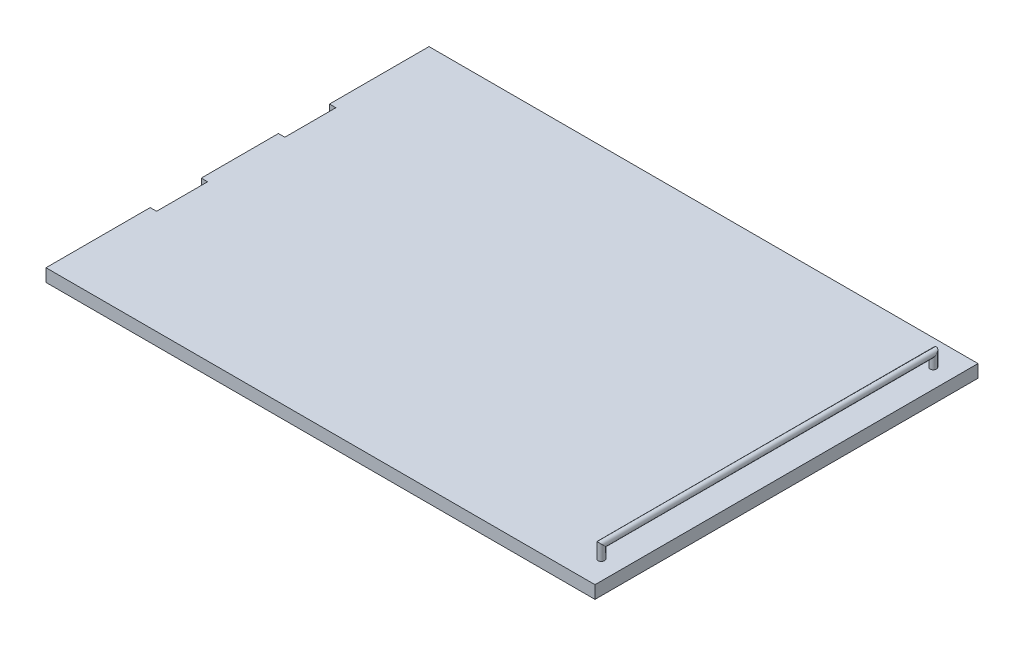
SolidWorks part; units mm, degrees
ref_plane "Front Plane" through (0, 0, 0) normal (0, 0, 1) x (1, 0, 0)
ref_plane "Top Plane" through (0, 0, 0) normal (0, 1, 0) x (1, 0, 0)
ref_plane "Right Plane" through (0, 0, 0) normal (1, 0, 0) x (0, 0, -1)
sketch "Sketch1" plane through (0, 0, 0) normal (0, 1, 0) x (1, 0, 0)
  line L1 (-546.1, -381) -> (546.1, -381)
  line L2 (-546.1, -381) -> (-546.1, 381)
  line L3 (-546.1, 381) -> (546.1, 381)
  line L4 (546.1, -381) -> (546.1, 381)
  line L5 (-546.1, -381) -> (546.1, 381) construction
  line L6 (-546.1, 381) -> (546.1, -381) construction
  point P0 (0, 0)
  dimension "D1" = 762
  dimension "D2" = 1092.2
extrude "Boss-Extrude1" add sketch "Sketch1" along normal blind 25.4
sketch "Sketch2" plane through (0, 25.4, 0) normal (0, 1, 0) x (1, 0, 0)
  line L0 (-546.1, 183.0439) -> (-546.1, 132.2439)
  line L1 (-546.1, 381) -> (-546.1, -381) construction
  line L2 (-546.1, 132.2439) -> (-546.1, 81.4439)
  line L3 (-546.1, -122.9273) -> (-546.1, -173.7273)
  line L6 (-546.1, -122.9273) -> (-546.1, -72.1273)
  line L9 (-546.1, 183.0439) -> (-533.4, 183.0439)
  line L10 (-533.4, 183.0439) -> (-533.4, 81.4439)
  line L11 (-533.4, 81.4439) -> (-546.1, 81.4439)
  line L12 (-546.1, -72.1273) -> (-533.4, -72.1273)
  line L13 (-533.4, -72.1273) -> (-533.4, -173.7273)
  line L14 (-533.4, -173.7273) -> (-546.1, -173.7273)
  dimension "D1" = 50.8
  dimension "D2" = 12.7
  dimension "D3" = 12.7
extrude "Cut-Extrude1" cut sketch "Sketch2" against normal through all
ref_plane "Plane1" through (508, 0, 0) normal (1, 0, 0) x (0, 0, -1)
sketch "Sketch3" plane through (508, 0, 0) normal (1, 0, 0) x (0, 0, -1)
  line L1 (-381, 25.4) -> (381, 25.4) construction
  line L3 (-330.2, 25.4) -> (-330.2, 50.8)
  line L4 (-330.2, 50.8) -> (330.2, 50.8)
  line L5 (330.2, 50.8) -> (330.2, 25.4)
  dimension "D2" = 25.4
sweep "Sweep1" add path "Sketch3" circular profile diameter 12.7 parameters "D3"=12.7
